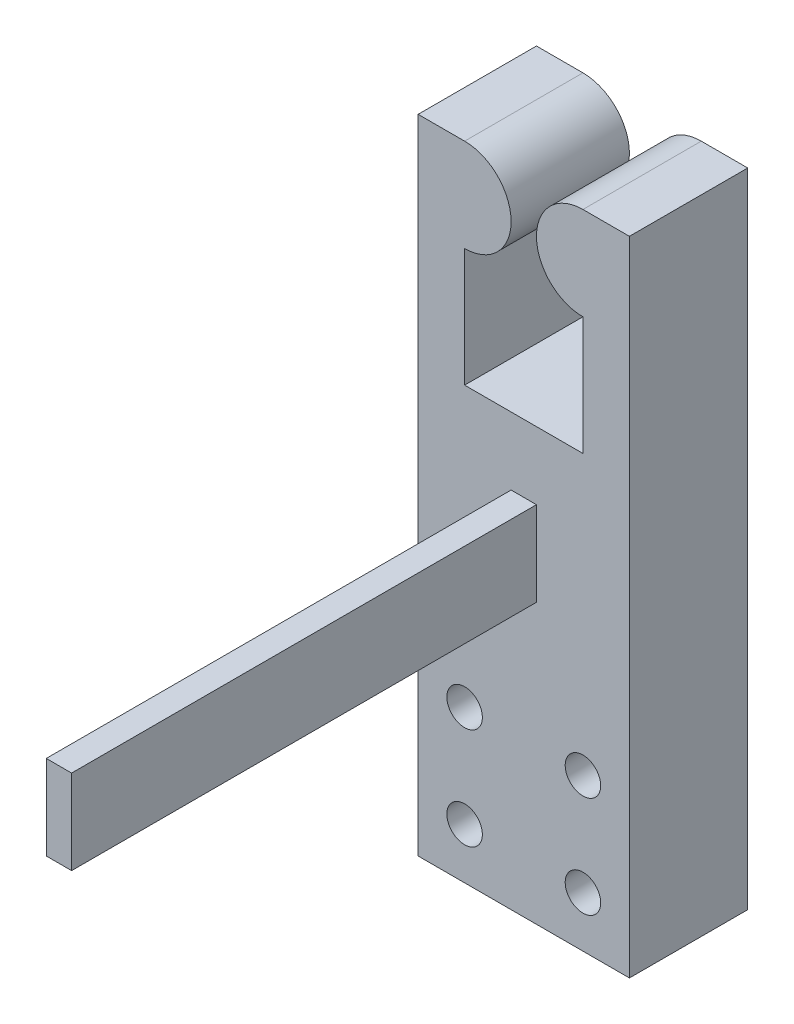
SolidWorks part; units mm, degrees
material "AISI 304"
ref_plane "Front" through (0, 0, 0) normal (0, 0, 1) x (1, 0, 0)
ref_plane "Top" through (0, 0, 0) normal (0, 1, 0) x (1, 0, 0)
ref_plane "Right" through (0, 0, 0) normal (1, 0, 0) x (0, 0, -1)
sketch "草图1" plane through (0, 0, 0) normal (0, 0, 1) x (1, 0, 0)
  line L1 (12.5, -38) -> (-12.5, -38)
  line L2 (12.5, -38) -> (12.5, 38)
  line L3 (12.5, 38) -> (-12.5, 38)
  line L4 (-12.5, -38) -> (-12.5, 38)
  line L5 (12.5, -38) -> (-12.5, 38) construction
  line L6 (12.5, 38) -> (-12.5, -38) construction
  point P0 (0, 0)
  dimension "D1" = 25
  dimension "D2" = 76
extrude "凸台-拉伸1" add sketch "草图1" along normal blind 14
sketch "草图2" plane through (0, 0, 14) normal (0, 0, 1) x (1, 0, 0)
  line L1 (-1.5, -5) -> (1.5, -5)
  line L2 (-1.5, -5) -> (-1.5, 5)
  line L3 (-1.5, 5) -> (1.5, 5)
  line L4 (1.5, -5) -> (1.5, 5)
  line L5 (-1.5, -5) -> (1.5, 5) construction
  line L6 (-1.5, 5) -> (1.5, -5) construction
  point P0 (0, 0)
  dimension "D1" = 3
  dimension "D2" = 10
extrude "凸台-拉伸2" add sketch "草图2" along normal blind 55
sketch "草图3" plane through (0, 0, 14) normal (0, 0, 1) x (1, 0, 0)
  line L0 (-12.5, -38) -> (12.5, -38) construction
  line L1 (0, 0) -> (0, -13.7633) construction
  circle A0 centre (-7, -20) radius 2.1
  circle A2 centre (-7, -32) radius 2.1
  circle A3 centre (7, -32) radius 2.1
  circle A4 centre (7, -20) radius 2.1
  dimension "D3" = 4.2
  dimension "D4" = 4.2
  dimension "D1" = 12
  dimension "D2" = 7
  dimension "D5" = 6
extrude "切除-拉伸1" cut sketch "草图3" against normal through all
sketch "草图4" plane through (0, 0, 14) normal (0, 0, 1) x (1, 0, 0)
  circle A0 centre (-7, -20) radius 3
  circle A1 centre (7, -20) radius 3
  circle A2 centre (-7, -32) radius 3
  circle A3 centre (7, -32) radius 3
  dimension "D1" = 6
  dimension "D2" = 6
  dimension "D3" = 6
  dimension "D4" = 6
sketch "草图5" plane through (0, 0, 14) normal (0, 0, 1) x (1, 0, 0)
  line L0 (-12.5, 38) -> (-12.5, -38) construction
  line L2 (12.5, 38) -> (-12.5, 38) construction
  line L3 (0, 0) -> (0, 17.7961) construction
  line L4 (-7, 13) -> (7, 13)
  line L5 (1.5, 5) -> (-1.5, 5) construction
  line L6 (-7, 27) -> (-7, 13)
  line L7 (7, 27) -> (7, 13)
  line L8 (-7, 38) -> (7, 38)
  arc A0 (-7, 27) -> (-7, 38) centre (-7, 32.5) ccw
  arc A1 (7, 27) -> (7, 38) centre (7, 32.5) cw
  point P19 (0, 13)
  dimension "D1" = 11
  dimension "D2" = 8
extrude "切除-拉伸3" cut sketch "草图5" against normal through all
sketch "草图6" plane through (0, 0, 0) normal (0, 0, -1) x (-1, 0, 0)
  circle A0 centre (7, -20) radius 3 construction
  circle A1 centre (7, -20) radius 3
  circle A2 centre (-7, -20) radius 3 construction
  circle A3 centre (-7, -20) radius 3
  circle A4 centre (-7, -32) radius 3 construction
  circle A5 centre (-7, -32) radius 3
  circle A6 centre (7, -32) radius 3 construction
  circle A7 centre (7, -32) radius 3
extrude "切除-拉伸4" cut sketch "草图6" against normal blind 5
